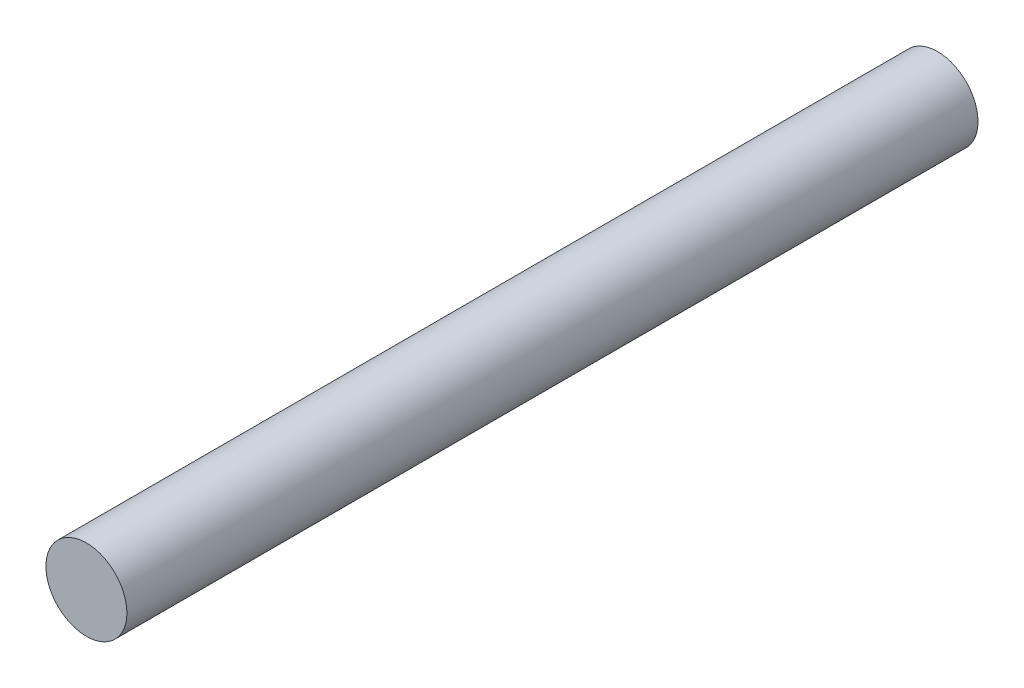
SolidWorks part; units mm, degrees
material "Generic Tool Steel"
ref_plane "Front Plane" through (0, 0, 0) normal (0, 0, 1) x (1, 0, 0)
ref_plane "Top Plane" through (0, 0, 0) normal (0, 1, 0) x (1, 0, 0)
ref_plane "Right Plane" through (0, 0, 0) normal (1, 0, 0) x (0, 0, -1)
sketch "Sketch1" plane through (0, 0, 0) normal (0, 0, 1) x (1, 0, 0)
  circle A0 centre (0, 0) radius 1.9029
  dimension "D1" = 3.8058
extrude "Boss-Extrude1" add sketch "Sketch1" along normal mid plane 40
